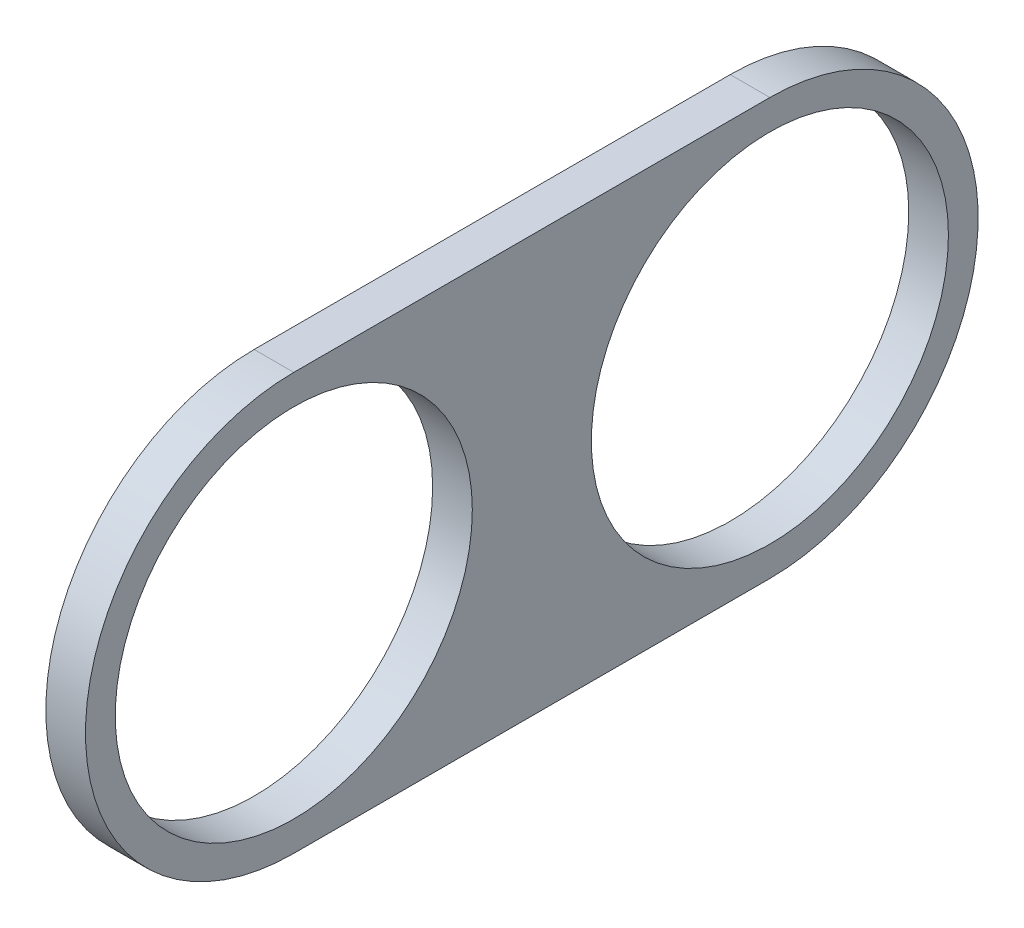
SolidWorks part; units mm, degrees
material "6061-T6 (SS)"
ref_plane "Front" through (0, 0, 0) normal (0, 0, 1) x (1, 0, 0)
ref_plane "Top" through (0, 0, 0) normal (0, 1, 0) x (1, 0, 0)
ref_plane "Right" through (0, 0, 0) normal (1, 0, 0) x (0, 0, -1)
sketch "Sketch1" plane through (0, 0, 0) normal (1, 0, 0) x (0, 0, -1)
  line L0 (-19.05, 0) -> (19.05, 0) construction
  line L1 (-19.05, 16.6687) -> (19.05, 16.6688)
  line L2 (-19.05, -16.6687) -> (19.05, -16.6687)
  arc A0 (-19.05, 16.6687) -> (-19.05, -16.6687) centre (-19.05, 0) ccw
  arc A1 (19.05, -16.6687) -> (19.05, 16.6688) centre (19.05, 0) ccw
  circle A2 centre (19.05, 0) radius 14.2875
  circle A3 centre (-19.05, 0) radius 14.2875
  point P2 (0, 0)
  dimension "D1" = 2.3812
  dimension "D2" = 28.575
  dimension "D3" = 38.1
extrude "Boss-Extrude1" add sketch "Sketch1" along normal blind 3.175
